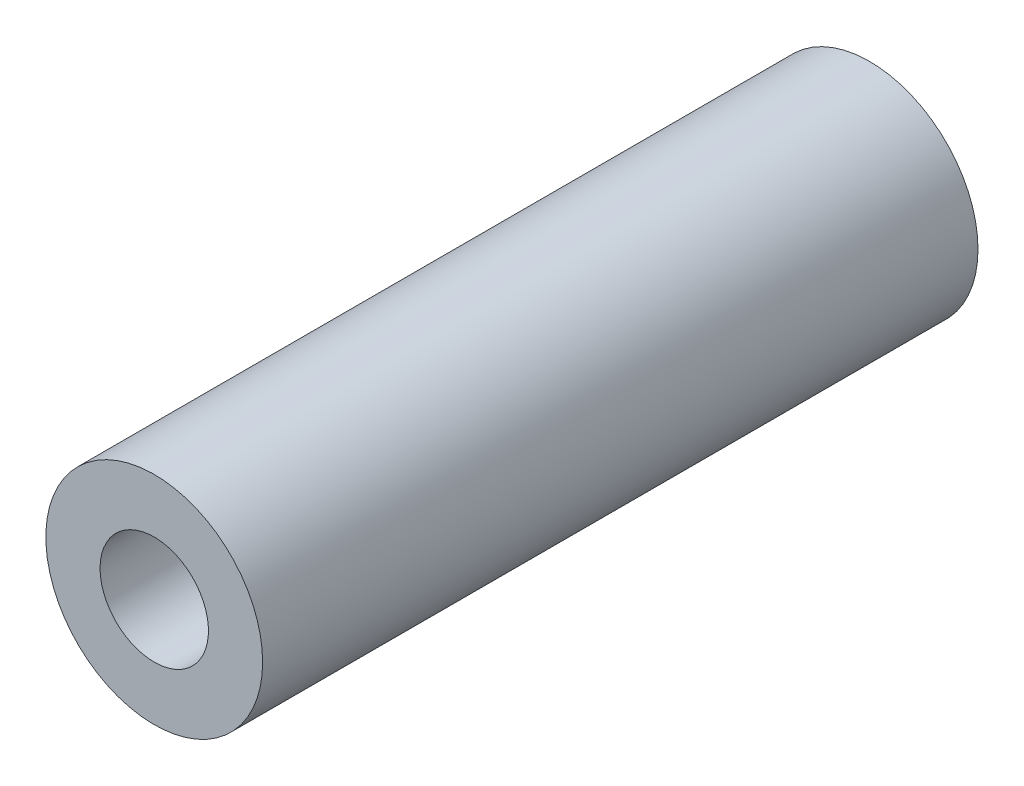
SolidWorks part; units mm, degrees
material "ABS PC"
ref_plane "Front Plane" through (0, 0, 0) normal (0, 0, 1) x (1, 0, 0)
ref_plane "Top Plane" through (0, 0, 0) normal (0, 1, 0) x (1, 0, 0)
ref_plane "Right Plane" through (0, 0, 0) normal (1, 0, 0) x (0, 0, -1)
sketch "Sketch1" plane through (0, 0, 0) normal (0, 0, 1) x (1, 0, 0)
  circle A0 centre (0, 0) radius 5
  dimension "D1" = 10
extrude "Boss-Extrude1" add sketch "Sketch1" along normal blind 33
sketch "Sketch2" plane through (0, 0, 0) normal (0, 0, -1) x (-1, 0, 0)
  circle A0 centre (0, 0) radius 2.5
  dimension "D1" = 5
extrude "Cut-Extrude1" cut sketch "Sketch2" against normal through all
